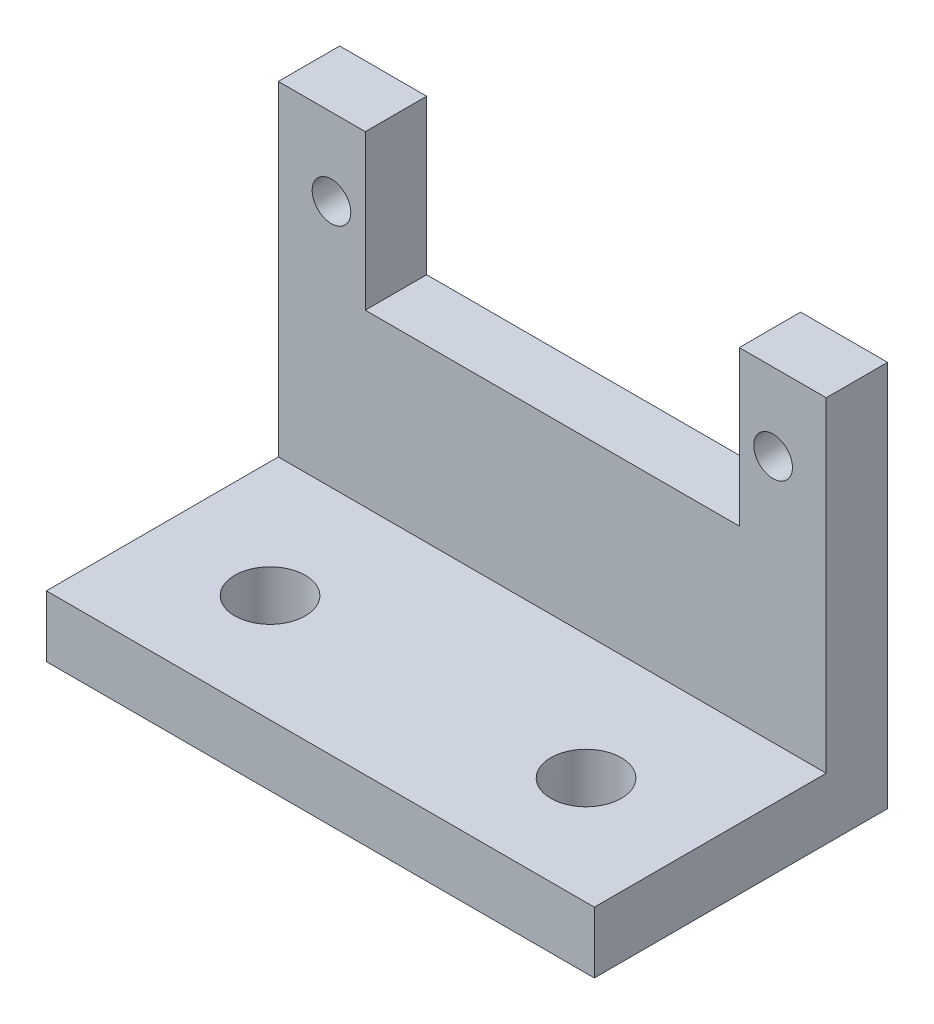
SolidWorks part; units mm, degrees
ref_plane "Front Plane" through (0, 0, 0) normal (0, 0, 1) x (1, 0, 0)
ref_plane "Top Plane" through (0, 0, 0) normal (0, 1, 0) x (1, 0, 0)
ref_plane "Right Plane" through (0, 0, 0) normal (1, 0, 0) x (0, 0, -1)
sketch "Sketch1" plane through (0, 0, 0) normal (0, 0, 1) x (1, 0, 0)
  line L0 (0, 8) -> (0, 0)
  line L1 (0, 8) -> (4.5, 8)
  line L2 (4.5, 8) -> (4.5, 0)
  line L3 (4.5, 0) -> (23.85, 0)
  line L4 (23.85, 0) -> (23.85, 8)
  line L5 (23.85, 8) -> (28.35, 8)
  line L6 (28.35, 8) -> (28.35, -12)
  line L7 (28.35, -12) -> (0, -12)
  line L8 (0, -12) -> (0, 0)
  line L12 (0, 4) -> (28.35, 4) construction
  circle A0 centre (2.75, 4) radius 1
  circle A1 centre (25.6, 4) radius 1
  dimension "D5" = 2
  dimension "D6" = 2
  dimension "D15" = 1.75
  dimension "D1" = 4.5
  dimension "D2" = 4.5
  dimension "D3" = 8
  dimension "D4" = 8
  dimension "D7" = 22.85
  dimension "D8" = 12
  dimension "D16" = 1.75
extrude "Boss-Extrude1" add sketch "Sketch1" along normal blind 3.175
sketch "Sketch2" plane through (0, 0, 3.175) normal (0, 0, 1) x (1, 0, 0)
  line L0 (28.35, -12) -> (28.35, 8) construction
  line L1 (0, -12) -> (28.35, -12)
  line L2 (0, -12) -> (0, -8.825)
  line L3 (0, -8.825) -> (28.35, -8.825)
  line L4 (28.35, -12) -> (28.35, -8.825)
  dimension "D1" = 3.175
extrude "Boss-Extrude2" add sketch "Sketch2" along normal blind 12
sketch "Sketch3" plane through (0, -8.825, 0) normal (0, 1, 0) x (1, 0, 0)
  line L0 (6, -9.6033) -> (22.35, -9.6033) construction
  line L1 (28.35, -15.175) -> (0, -15.175) construction
  line L2 (28.35, -15.175) -> (28.35, -3.175) construction
  line L3 (0, -15.175) -> (0, -3.175) construction
  line L4 (28.35, -3.175) -> (0, -3.175) construction
  circle A0 centre (6, -9.6033) radius 1.825
  circle A1 centre (22.35, -9.6033) radius 1.825
  dimension "D1" = 3.65
  dimension "D2" = 3.65
  dimension "D3" = 6
  dimension "D4" = 6
  dimension "D5" = 6.4283
extrude "Cut-Extrude1" cut sketch "Sketch3" against normal up to surface (3.175 mm away) up to face at (14.175, -12, 7.5875)
